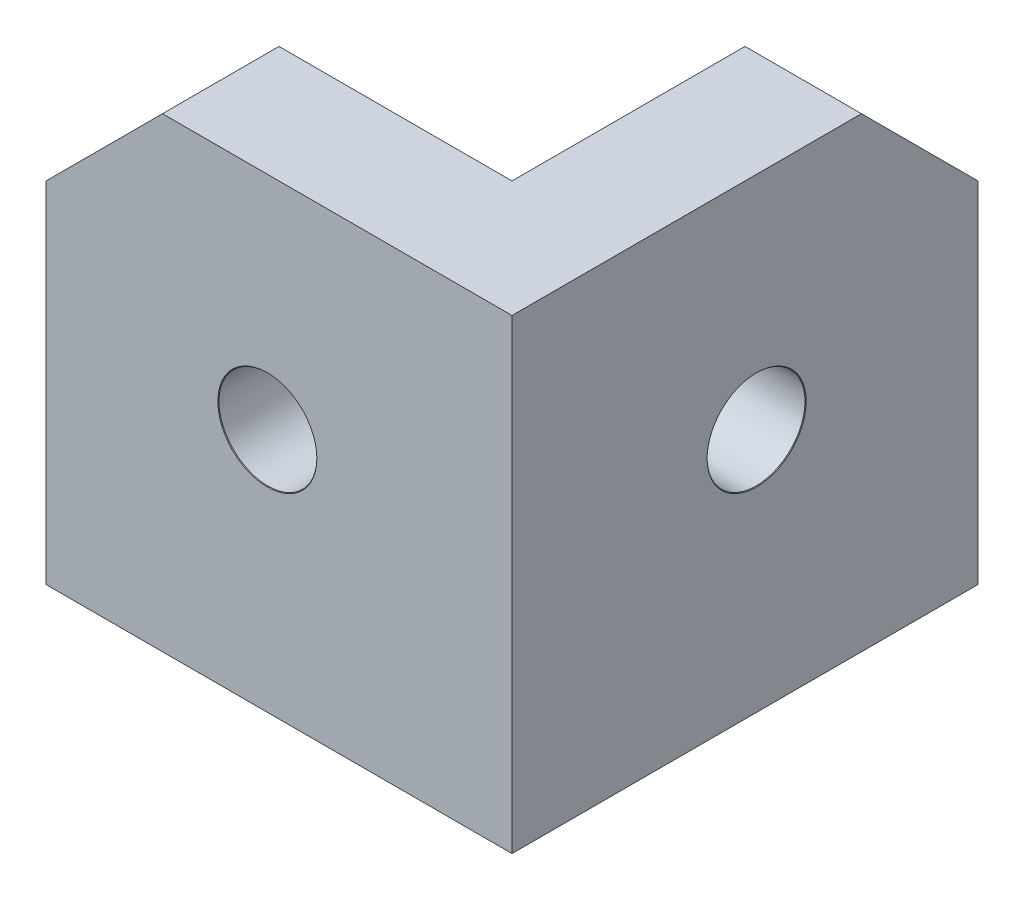
SolidWorks part; units mm, degrees
ref_plane "Front Plane" through (0, 0, 0) normal (0, 0, 1) x (1, 0, 0)
ref_plane "Top Plane" through (0, 0, 0) normal (0, 1, 0) x (1, 0, 0)
ref_plane "Right Plane" through (0, 0, 0) normal (1, 0, 0) x (0, 0, -1)
sketch "Sketch1" plane through (0, 0, 0) normal (0, 1, 0) x (1, 0, 0)
  line L0 (20, 0) -> (9.5, 0)
  line L1 (0, 0) -> (20, 0)
  line L2 (0, 0) -> (0, 20)
  line L3 (0, 20) -> (20, 20)
  line L4 (20, 0) -> (20, 20)
  line L5 (9.5, 0) -> (9.5, 10.5)
extrude "Boss-Extrude1" add sketch "Sketch1" along normal blind 5
hole_wizard "Tap Drill for M5x0.8 Tap1" positions "Sketch2" profile "Sketch3" hole size "M5x0.8" standard "ANSI Metric" end condition through all
sketch "Sketch2" plane through (0, 0, 0) normal (0, -1, 0) x (-1, 0, 0)
  point P0 (-9.5, 10.5)
sketch "Sketch3" plane through (9.5, 0, -10.5) normal (1, 0, 0) x (0, 0, -1)
  line L0 (0, 0) -> (0, 5)
  line L1 (0, 5) -> (2.1, 5)
  line L2 (2.1, 5) -> (2.1, 0.025)
  line L3 (2.1, 0.025) -> (2.125, 0)
  line L5 (2.125, 0) -> (0, 0)
  line L6 (-2.1, 0.025) -> (-2.125, 0) construction
  line L11 (0, -6.35) -> (0, 107.95) construction
  dimension "Thru Hole Dia." = 4.2
  dimension "Thru Hole Depth" = 5
  dimension "Near C'Sink Dia." = 4.25
  dimension "Near C'Sink Angle" = 90
sketch "Sketch4" plane through (0, 5, 0) normal (0, 1, 0) x (1, 0, 0)
  line L0 (20, 0) -> (0, 0) construction
  line L1 (20, 20) -> (15, 20)
  line L2 (20, 20) -> (20, 0)
  line L3 (20, 0) -> (15, 0)
  line L4 (15, 20) -> (15, 0)
  line L5 (0, 0) -> (0, 20) construction
  line L6 (20, 0) -> (0, 0)
  line L7 (20, 0) -> (20, 5)
  line L8 (20, 5) -> (0, 5)
  line L9 (0, 0) -> (0, 5)
  line M6 (0, 0) -> (20, 0)
  line M7 (20, 0) -> (20, 20)
  line M8 (20, 20) -> (0, 20)
  line M9 (0, 20) -> (0, 0)
extrude "Boss-Extrude2" add sketch "Sketch4" along normal blind 15 contours L8 L2 L4 M8 | L8 L4 M7 M6 | L4 L8 M9 M6
sketch "Sketch5" plane through (0, 0, 0) normal (0, 0, 1) x (1, 0, 0)
  line L0 (20, 0) -> (9.5, 0)
  line L1 (0, 0) -> (20, 0) construction
  line L2 (9.5, 0) -> (9.5, 10.5)
hole_wizard "Tap Drill for M5x0.8 Tap2" positions "Sketch6" profile "Sketch7" hole size "M5x0.8" standard "ANSI Metric" end condition through all
sketch "Sketch6" plane through (0, 0, 0) normal (0, 0, 1) x (1, 0, 0)
  point P0 (9.5, 10.5)
sketch "Sketch7" plane through (9.5, 10.5, 0) normal (1, 0, 0) x (0, -1, 0)
  line L0 (0, 0) -> (0, 20)
  line L1 (0, 20) -> (2.1, 20)
  line L2 (2.1, 20) -> (2.1, 0.025)
  line L3 (2.1, 0.025) -> (2.125, 0)
  line L5 (2.125, 0) -> (0, 0)
  line L6 (-2.1, 0.025) -> (-2.125, 0) construction
  line L11 (0, -6.35) -> (0, 107.95) construction
  dimension "Thru Hole Dia." = 4.2
  dimension "Thru Hole Depth" = 20
  dimension "Near C'Sink Dia." = 4.25
  dimension "Near C'Sink Angle" = 90
sketch "Sketch8" plane through (20, 0, 0) normal (1, 0, 0) x (0, 0, -1)
  line L0 (0, 0) -> (10.5, 0)
  line L1 (0, 0) -> (10.5, 0) construction
  line L2 (0, 0) -> (20, 0) construction
  line L3 (10.5, 0) -> (10.5, 10.5)
hole_wizard "Tap Drill for M5x0.8 Tap3" positions "Sketch9" profile "Sketch10" hole size "M5x0.8" standard "ANSI Metric" end condition through all
sketch "Sketch9" plane through (20, 0, 0) normal (1, 0, 0) x (0, 0, -1)
  point P0 (10.5, 10.5)
sketch "Sketch10" plane through (20, 10.5, -10.5) normal (0, 1, 0) x (0, 0, -1)
  line L0 (0, 0) -> (0, 20)
  line L1 (0, 20) -> (2.1, 20)
  line L2 (2.1, 20) -> (2.1, 0.025)
  line L3 (2.1, 0.025) -> (2.125, 0)
  line L5 (2.125, 0) -> (0, 0)
  line L6 (-2.1, 0.025) -> (-2.125, 0) construction
  line L11 (0, -6.35) -> (0, 107.95) construction
  dimension "Thru Hole Dia." = 4.2
  dimension "Thru Hole Depth" = 20
  dimension "Near C'Sink Dia." = 4.25
  dimension "Near C'Sink Angle" = 90
chamfer "Chamfer1" distance 5 angle 45 3 edges at (0, 2.5, -20) (0, 20, -2.5) (17.5, 20, -20)
